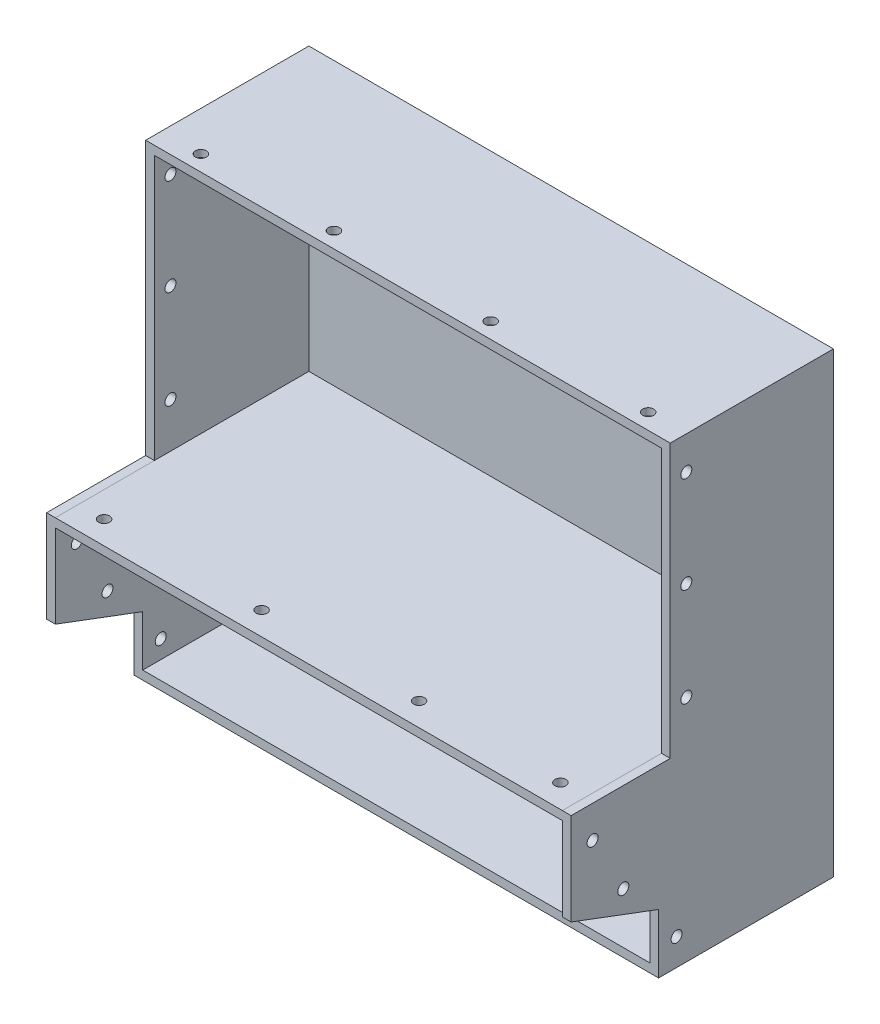
SolidWorks part; units mm, degrees
material "Custom Plastic"
ref_plane "X-Y Datum" through (0, 0, 0) normal (0, 0, 1) x (1, 0, 0)
ref_plane "X-Z Datum" through (0, 0, 0) normal (0, 1, 0) x (1, 0, 0)
ref_plane "Y-Z Datum" through (0, 0, 0) normal (1, 0, 0) x (0, 0, -1)
sketch "Sketch1" plane through (0, 0, 0) normal (0, 0, 1) x (1, 0, 0)
  line L1 (-95.25, -83.058) -> (95.25, -83.058)
  line L2 (-95.25, -83.058) -> (-95.25, 83.058)
  line L3 (-95.25, 83.058) -> (95.25, 83.058)
  line L4 (95.25, -83.058) -> (95.25, 83.058)
  line L5 (-95.25, -83.058) -> (95.25, 83.058) construction
  line L6 (-95.25, 83.058) -> (95.25, -83.058) construction
  point P0 (0, 0)
  dimension "D1" = 166.116
  dimension "D2" = 190.5
extrude "Boss-Extrude1" add sketch "Sketch1" along normal blind 95.25
sketch "Sketch3" plane through (0, 0, 95.25) normal (0, 0, 1) x (1, 0, 0)
  line L0 (-92.075, -49.9618) -> (92.075, -49.9618)
  line L1 (92.075, -61.8913) -> (95.25, -61.8913)
  line L2 (-92.075, -61.8913) -> (92.075, -61.8913)
  line L3 (95.25, -83.058) -> (95.25, 83.058) construction
  line L4 (-92.075, -61.8913) -> (-92.075, -79.883)
  line L5 (-95.25, -49.9618) -> (-95.25, -61.8913)
  line L6 (92.075, -61.8913) -> (92.075, -79.883)
  line L7 (-95.25, 83.058) -> (-95.25, -83.058) construction
  line L8 (-122.0928, 3.2687) -> (-122.1486, 3.2687)
  line L9 (92.075, -79.883) -> (76.2531, -79.883)
  line L13 (-95.25, 32.8917) -> (-92.075, 32.8917)
  line L15 (-122.0786, -16.0951) -> (-122.1486, -16.0951)
  line L17 (95.25, -49.9618) -> (92.075, -49.9618)
  line L18 (-92.075, -79.883) -> (76.2531, -79.883)
  line L21 (-92.075, -49.9618) -> (-95.25, -49.9618)
  line L23 (-81.0858, 79.883) -> (83.8833, 79.883)
  line L25 (-81.0858, 79.883) -> (-92.075, 79.883)
  line L26 (-92.075, 79.883) -> (-92.075, -16.0951)
  line L28 (95.25, 48.6627) -> (92.075, 48.6627)
  line L30 (83.8833, 79.883) -> (92.075, 79.883)
  line L31 (92.075, 79.883) -> (92.075, -16.0951)
  line L33 (-92.075, -16.0951) -> (92.075, -16.0951)
  line L34 (95.25, -49.9618) -> (95.25, -61.8913)
  line L35 (-95.25, -61.8913) -> (-92.075, -61.8913)
extrude "Cut-Extrude1" cut sketch "Sketch3" against normal blind 92.075
sketch "Sketch15" plane through (0, 0, 95.25) normal (0, 0, 1) x (1, 0, 0)
  line L1 (-95.25, 83.058) -> (-95.25, -83.058) construction
  line L3 (95.25, -83.058) -> (95.25, 83.058) construction
  line L4 (95.25, -16.1093) -> (95.25, 83.058)
  line L5 (95.25, 83.058) -> (-95.25, 83.058)
  line L6 (-95.25, 83.058) -> (-95.25, -16.1093)
  line L10 (95.25, -16.1093) -> (92.075, -16.0951)
  line L11 (92.075, -16.0951) -> (92.075, 79.883)
  line L12 (92.075, 79.883) -> (-92.075, 79.883)
  line L13 (-92.075, 79.883) -> (-92.075, -16.0951)
  line L14 (-92.075, -16.0951) -> (92.075, -16.0951) construction
  line L15 (-92.075, 79.883) -> (-92.075, -16.0951) construction
  line L16 (-95.25, -16.1093) -> (-92.075, -16.0951)
extrude "Cut-Extrude5" cut sketch "Sketch15" against normal blind 35.9842
sketch "Sketch17" plane through (0, 0, 95.25) normal (0, 0, 1) x (1, 0, 0)
  line L0 (-95.25, -49.5836) -> (-95.25, -83.058)
  line L2 (-95.25, -83.058) -> (95.25, -83.058)
  line L3 (-95.25, -16.1093) -> (-95.25, -83.058) construction
  line L4 (95.25, -83.058) -> (95.25, -16.1093) construction
  line L5 (95.25, -83.058) -> (95.25, -49.5836)
  line L6 (-95.25, -49.5836) -> (95.25, -49.5836)
extrude "Cut-Extrude6" cut sketch "Sketch17" against normal blind 31.75
sketch "Sketch18" plane through (-95.25, 0, 0) normal (-1, 0, 0) x (0, 0, 1)
  line L0 (63.5, -49.5836) -> (63.5, -61.5061)
  line L1 (63.5, -49.5836) -> (63.5, -83.058) construction
  line L2 (63.5, -61.5061) -> (95.25, -49.5836)
  line L3 (95.25, -49.5836) -> (63.5, -49.5836)
extrude "Boss-Extrude8" add sketch "Sketch18" against normal blind 190.5
sketch "Sketch19" plane through (0, 0, 95.25) normal (0, 0, 1) x (1, 0, 0)
  line L0 (-92.075, -19.2701) -> (-92.075, -49.5836)
  line L2 (95.25, -49.5836) -> (-95.25, -49.5836) construction
  line L4 (92.075, -19.2701) -> (92.075, -49.5836)
  line L6 (92.075, -49.5836) -> (-92.075, -49.5836)
  line L8 (-92.075, -19.2701) -> (92.075, -19.2701)
extrude "Cut-Extrude7" cut sketch "Sketch19" against normal blind 92.075
sketch "Sketch20" plane through (0, -74.8032, 28.0894) normal (0, -0.9362, 0.3515) x (1, 0, 0)
  line L2 (-92.075, -3.8019) -> (-92.075, 82.3961) construction
  line L4 (-92.075, 71.7396) -> (92.075, 71.7396) construction
  line L6 (-92.075, 71.7396) -> (92.075, 71.7396)
  line L12 (92.075, -3.8019) -> (92.075, 82.3961) construction
  line L13 (95.25, 71.7396) -> (92.075, 71.7396) construction
  line L15 (-92.075, 71.7396) -> (-92.075, 37.8249)
  line L16 (95.25, 37.8249) -> (-95.25, 37.8249) construction
  line L17 (92.075, 71.7396) -> (92.075, 37.8249)
  line L18 (92.075, 37.8249) -> (-92.075, 37.8249)
extrude "Cut-Extrude8" cut sketch "Sketch20" against normal blind 13.175
sketch "Sketch21" plane through (0, 0, 63.5) normal (0, 0, 1) x (1, 0, 0)
  line L0 (-92.075, -61.5061) -> (-92.075, -49.5836)
  line L2 (-92.075, -49.5836) -> (92.075, -49.5836)
  line L4 (92.075, -49.5836) -> (92.075, -61.5061)
  line L6 (-92.075, -61.5061) -> (-92.075, -79.883)
  line L7 (-92.075, -79.883) -> (92.075, -79.883)
  line L8 (92.075, -79.883) -> (92.075, -61.5061)
extrude "Cut-Extrude9" cut sketch "Sketch21" against normal blind 60.325
sketch "Sketch23" plane through (0, -83.058, 0) normal (0, -1, 0) x (1, 0, 0)
  circle A4 centre (-82.8492, 55.0007) radius 2
  circle A5 centre (-25.472, 55.0007) radius 2
  circle A6 centre (31.5236, 55.0007) radius 2
  circle A7 centre (82.8147, 55.0007) radius 2
extrude "Cut-Extrude10" cut sketch "Sketch23" against normal blind 2.54
sketch "Sketch24" plane through (0, 83.058, 0) normal (0, 1, 0) x (1, 0, 0)
  line L0 (81.5233, -53.5508) -> (-86.3243, -53.5508) construction
  line L1 (95.25, -59.2658) -> (-95.25, -59.2658) construction
  circle A0 centre (81.5233, -53.5508) radius 2
  circle A3 centre (24.3357, -53.5508) radius 2
  circle A4 centre (-32.5907, -53.5508) radius 2
  circle A7 centre (-80.8952, -53.5508) radius 2
  dimension "D1" = 5.715
extrude "Cut-Extrude11" cut sketch "Sketch24" against normal blind 2.54
sketch "Sketch25" plane through (95.25, 0, 0) normal (1, 0, 0) x (0, 0, -1)
  circle A0 centre (-53.4238, 70.993) radius 2
  circle A1 centre (-53.4238, 35.941) radius 2
  circle A4 centre (-53.4238, 0.889) radius 2 [skipped]
  circle A6 centre (-53.4238, 0.2178) radius 2
  dimension "D2" = 3
extrude "Cut-Extrude12" cut sketch "Sketch25" against normal through all
sketch "Sketch26" plane through (0, -16.0951, 0) normal (0, 1, 0) x (1, 0, 0)
  line L1 (92.075, -59.2658) -> (92.075, -95.25) construction
  line L2 (92.075, -63.7108) -> (-92.075, -63.7108)
  line L3 (-92.075, -59.2658) -> (-92.075, -95.25) construction
  line L5 (-92.075, -79.375) -> (92.075, -79.375)
sketch "Sketch27" plane through (0, -16.0951, 0) normal (0, 1, 0) x (1, 0, 0)
  circle A0 centre (82.9278, -86.8228) radius 2
  circle A8 centre (31.5919, -86.8228) radius 2
  circle A11 centre (-25.6023, -86.8228) radius 2
  circle A12 centre (-82.8005, -86.8228) radius 2
extrude "Cut-Extrude13" cut sketch "Sketch27" against normal blind 3.175
sketch "Sketch28" plane through (95.25, 0, 0) normal (1, 0, 0) x (0, 0, -1)
  circle A0 centre (-56.9612, -73.2851) radius 2
  circle A1 centre (-76.307, -48.5678) radius 2
  circle A2 centre (-87.4498, -27.7945) radius 2
extrude "Cut-Extrude15" cut sketch "Sketch28" against normal through all
